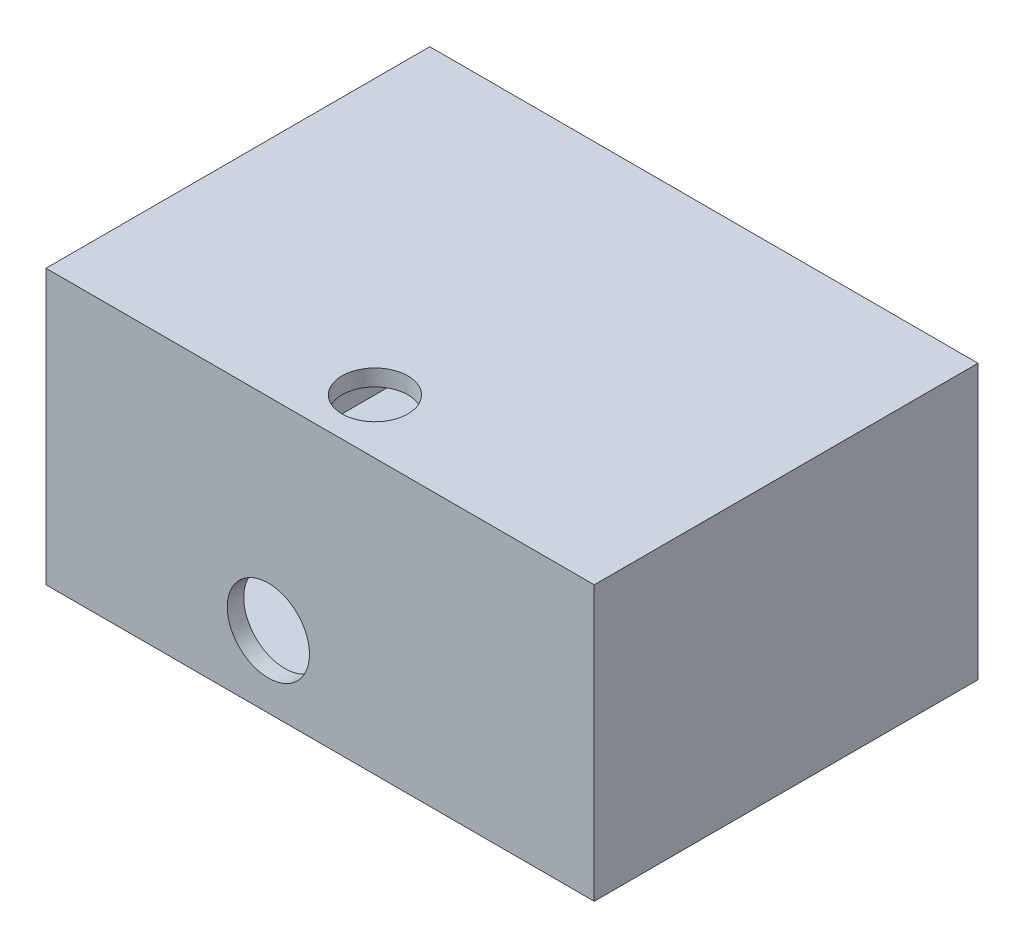
SolidWorks part; units mm, degrees
ref_plane "Plan de face" through (0, 0, 0) normal (0, 0, 1) x (1, 0, 0)
ref_plane "Plan de dessus" through (0, 0, 0) normal (0, 1, 0) x (1, 0, 0)
ref_plane "Plan de droite" through (0, 0, 0) normal (1, 0, 0) x (0, 0, -1)
sketch "Esquisse1" plane through (0, 0, 0) normal (0, 0, 1) x (1, 0, 0)
  line L1 (-50, 25) -> (50, 25)
  line L2 (-50, 25) -> (-50, -25)
  line L3 (-50, -25) -> (50, -25)
  line L4 (50, 25) -> (50, -25)
  line L5 (-50, 25) -> (50, -25) construction
  line L6 (-50, -25) -> (50, 25) construction
  point P0 (0, 0)
  dimension "D1" = 100
  dimension "D2" = 50
extrude "Boss.-Extru.1" add sketch "Esquisse1" along normal blind 70
shell "Coque1" thickness 3
sketch "Esquisse2" plane through (-47, 0, 0) normal (1, 0, 0) x (0, 0, -1)
  line L0 (-67, 25) -> (-3, 25) construction
  line L1 (-67, 25) -> (-3, 25)
  line L2 (-67, 22) -> (-3, 22)
  line L3 (-67, 25) -> (-67, -22) construction
  line L4 (-3, 25) -> (-3, -22) construction
  line L5 (-3, 25) -> (-3, 22)
  line L6 (-67, 25) -> (-67, 22)
  dimension "D1" = 3
extrude "Boss.-Extru.2" add sketch "Esquisse2" along normal through all
sketch "Esquisse3" plane through (0, 25, 0) normal (0, 1, 0) x (1, 0, 0)
  line L0 (50, 0) -> (-50, 0) construction
  circle A0 centre (0, -60) radius 6.015
  dimension "D1" = 12.03
  dimension "D2" = 60
extrude "Enlèv. mat.-Extru.1" cut sketch "Esquisse3" against normal blind 5
sketch "Esquisse4" plane through (0, 0, 70) normal (0, 0, 1) x (1, 0, 0)
  line L0 (-50, -25) -> (50, -25) construction
  line L1 (-50, 25) -> (-50, -25) construction
  circle A1 centre (-9.44, -11.95) radius 6
  dimension "D1" = 13.05
  dimension "D3" = 12
  dimension "D2" = 40.56
extrude "Enlèv. mat.-Extru.2" cut sketch "Esquisse4" against normal blind 5
sketch "Esquisse5" plane through (0, 0, 70) normal (0, 0, 1) x (1, 0, 0)
  circle A0 centre (-9.44, -11.95) radius 7.5
  dimension "D1" = 15
extrude "Enlèv. mat.-Extru.3" cut sketch "Esquisse5" against normal blind 10
